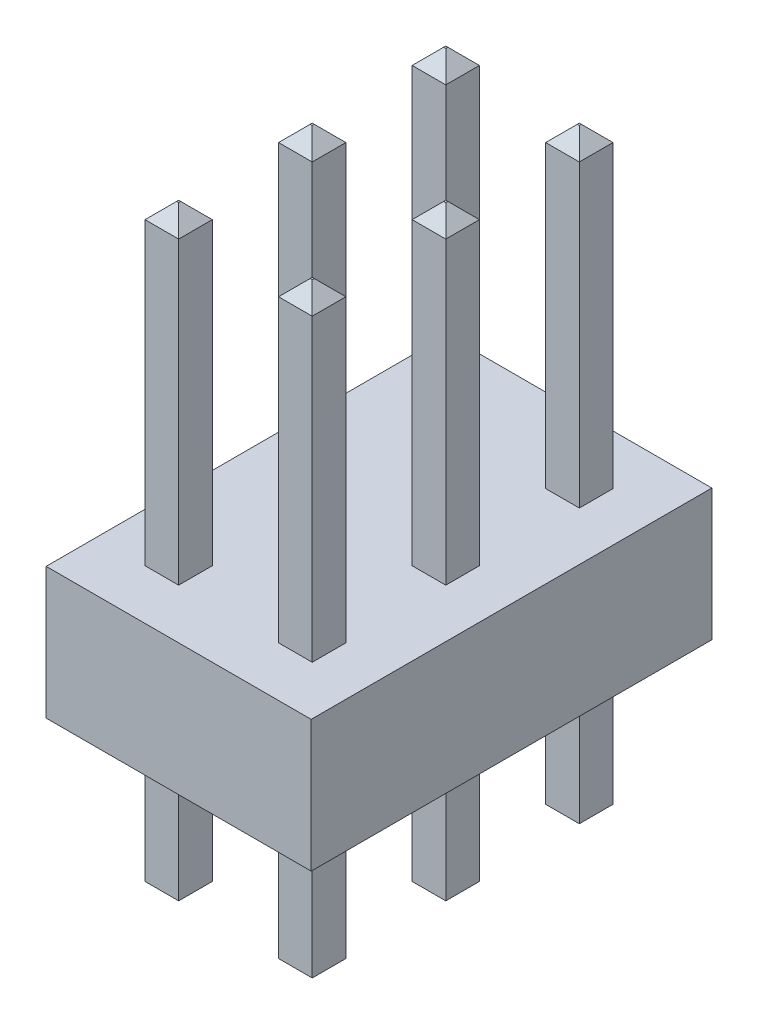
SolidWorks part; units mm, degrees
ref_plane "Vorne" through (0, 0, 0) normal (0, 0, 1) x (1, 0, 0)
ref_plane "Oben" through (0, 0, 0) normal (0, 1, 0) x (1, 0, 0)
ref_plane "Rechts" through (0, 0, 0) normal (1, 0, 0) x (0, 0, -1)
sketch "Skizze1" plane through (0, 0, 0) normal (0, 0, 1) x (1, 0, 0)
  line L1 (0, 0) -> (5.04, 0)
  line L2 (0, 0) -> (0, 2.5)
  line L3 (0, 2.5) -> (5.04, 2.5)
  line L4 (5.04, 0) -> (5.04, 2.5)
  dimension "D1" = 5.04
  dimension "D2" = 2.5
extrude "Aufsatz-Linear austragen1" add sketch "Skizze1" along normal blind 7.62
sketch "Skizze2" plane through (0, 2.5, 0) normal (0, 1, 0) x (1, 0, 0)
  line L0 (5.04, 0) -> (0, 0) construction
  line L1 (0, -7.62) -> (0, 0) construction
  line L2 (3.47, -0.95) -> (4.11, -0.95)
  line L3 (3.47, -0.95) -> (3.47, -1.59)
  line L4 (3.47, -1.59) -> (4.11, -1.59)
  line L5 (4.11, -0.95) -> (4.11, -1.59)
  line L6 (3.47, -0.95) -> (4.11, -1.59) construction
  line L7 (0.93, -0.95) -> (1.57, -0.95)
  line L8 (0.93, -0.95) -> (0.93, -1.59)
  line L9 (0.93, -1.59) -> (1.57, -1.59)
  line L10 (1.57, -0.95) -> (1.57, -1.59)
  line L11 (0.93, -0.95) -> (1.57, -1.59) construction
  line L12 (0.93, -1.59) -> (1.57, -0.95) construction
  line L13 (3.47, -1.59) -> (4.11, -0.95) construction
  line L14 (0.93, -3.49) -> (1.57, -3.49)
  line L15 (0.93, -3.49) -> (0.93, -4.13)
  line L16 (0.93, -4.13) -> (1.57, -4.13)
  line L17 (1.57, -3.49) -> (1.57, -4.13)
  line L18 (0.93, -3.49) -> (1.57, -4.13) construction
  line L19 (0.93, -4.13) -> (1.57, -3.49) construction
  line L20 (3.47, -3.49) -> (4.11, -3.49)
  line L21 (3.47, -3.49) -> (3.47, -4.13)
  line L22 (3.47, -4.13) -> (4.11, -4.13)
  line L23 (4.11, -3.49) -> (4.11, -4.13)
  line L24 (3.47, -3.49) -> (4.11, -4.13) construction
  line L25 (3.47, -4.13) -> (4.11, -3.49) construction
  line L26 (0.93, -6.03) -> (1.57, -6.03)
  line L27 (0.93, -6.03) -> (0.93, -6.67)
  line L28 (0.93, -6.67) -> (1.57, -6.67)
  line L29 (1.57, -6.03) -> (1.57, -6.67)
  line L30 (0.93, -6.03) -> (1.57, -6.67) construction
  line L31 (0.93, -6.67) -> (1.57, -6.03) construction
  line L32 (3.47, -6.03) -> (4.11, -6.03)
  line L33 (3.47, -6.03) -> (3.47, -6.67)
  line L34 (3.47, -6.67) -> (4.11, -6.67)
  line L35 (4.11, -6.03) -> (4.11, -6.67)
  line L36 (3.47, -6.03) -> (4.11, -6.67) construction
  line L37 (3.47, -6.67) -> (4.11, -6.03) construction
  point P4 (3.79, -1.27)
  point P5 (1.25, -1.27)
  point P16 (1.25, -3.81)
  point P21 (3.79, -3.81)
  point P26 (1.25, -6.35)
  point P31 (3.79, -6.35)
  dimension "D1" = 1.27
  dimension "D2" = 1.25
  dimension "D3" = 0.64
  dimension "D4" = 0.64
  dimension "D5" = 2
  dimension "D6" = 3
extrude "Aufsatz-Linear austragen2" add sketch "Skizze2" along normal blind 6
chamfer "Fase1" distance 0.3 angle 45 24 edges at (1.57, 8.5, 6.35) (1.25, 8.5, 6.67) (0.93, 8.5, 6.35) (1.25, 8.5, 6.03) (4.11, 8.5, 6.35) (3.79, 8.5, 6.67) (3.47, 8.5, 6.35) (3.79, 8.5, 6.03) (4.11, 8.5, 3.81) (3.79, 8.5, 4.13) (3.79, 8.5, 3.49) (3.47, 8.5, 3.81) (1.57, 8.5, 3.81) (1.25, 8.5, 4.13) (0.93, 8.5, 3.81) (1.25, 8.5, 3.49) (1.57, 8.5, 1.27) (1.25, 8.5, 1.59) (0.93, 8.5, 1.27) (1.25, 8.5, 0.95) (3.79, 8.5, 1.59) (3.47, 8.5, 1.27) (3.79, 8.5, 0.95) (4.11, 8.5, 1.27)
sketch "Skizze3" plane through (0, 0, 0) normal (0, -1, 0) x (1, 0, 0)
  line L0 (0, 7.62) -> (0, 0) construction
  line L1 (0.93, 0.95) -> (1.57, 0.95)
  line L2 (0.93, 0.95) -> (0.93, 1.59)
  line L3 (0.93, 1.59) -> (1.57, 1.59)
  line L4 (1.57, 0.95) -> (1.57, 1.59)
  line L5 (0.93, 0.95) -> (1.57, 1.59) construction
  line L6 (0.93, 1.59) -> (1.57, 0.95) construction
  line L7 (0, 0) -> (5.04, 0) construction
  line L8 (3.47, 0.95) -> (4.11, 0.95)
  line L9 (3.47, 0.95) -> (3.47, 1.59)
  line L10 (3.47, 1.59) -> (4.11, 1.59)
  line L11 (4.11, 0.95) -> (4.11, 1.59)
  line L12 (3.47, 0.95) -> (4.11, 1.59) construction
  line L13 (3.47, 1.59) -> (4.11, 0.95) construction
  line L14 (0.93, 3.49) -> (1.57, 3.49)
  line L15 (0.93, 3.49) -> (0.93, 4.13)
  line L16 (0.93, 4.13) -> (1.57, 4.13)
  line L17 (1.57, 3.49) -> (1.57, 4.13)
  line L18 (0.93, 3.49) -> (1.57, 4.13) construction
  line L19 (0.93, 4.13) -> (1.57, 3.49) construction
  line L20 (3.47, 3.49) -> (4.11, 3.49)
  line L21 (3.47, 3.49) -> (3.47, 4.13)
  line L22 (3.47, 4.13) -> (4.11, 4.13)
  line L23 (4.11, 3.49) -> (4.11, 4.13)
  line L24 (3.47, 3.49) -> (4.11, 4.13) construction
  line L25 (3.47, 4.13) -> (4.11, 3.49) construction
  line L26 (0.93, 6.03) -> (1.57, 6.03)
  line L27 (0.93, 6.03) -> (0.93, 6.67)
  line L28 (0.93, 6.67) -> (1.57, 6.67)
  line L29 (1.57, 6.03) -> (1.57, 6.67)
  line L30 (0.93, 6.03) -> (1.57, 6.67) construction
  line L31 (0.93, 6.67) -> (1.57, 6.03) construction
  line L32 (3.47, 6.03) -> (4.11, 6.03)
  line L33 (3.47, 6.03) -> (3.47, 6.67)
  line L34 (3.47, 6.67) -> (4.11, 6.67)
  line L35 (4.11, 6.03) -> (4.11, 6.67)
  line L36 (3.47, 6.03) -> (4.11, 6.67) construction
  line L37 (3.47, 6.67) -> (4.11, 6.03) construction
  point P0 (1.25, 1.27)
  point P11 (3.79, 1.27)
  point P16 (1.25, 3.81)
  point P21 (3.79, 3.81)
  point P26 (1.25, 6.35)
  point P31 (3.79, 6.35)
  dimension "D1" = 0.64
  dimension "D2" = 0.64
  dimension "D3" = 1.25
  dimension "D4" = 1.27
  dimension "D5" = 2
  dimension "D6" = 3
extrude "Aufsatz-Linear austragen3" add sketch "Skizze3" along normal blind 3
chamfer "Fase2" distance 0.3 angle 45 24 edges at (1.25, -3, 3.49) (0.93, -3, 3.81) (1.25, -3, 4.13) (1.57, -3, 3.81) (1.25, -3, 6.03) (0.93, -3, 6.35) (1.25, -3, 6.67) (1.57, -3, 6.35) (3.79, -3, 6.67) (3.47, -3, 6.35) (3.79, -3, 6.03) (4.11, -3, 6.35) (3.79, -3, 3.49) (3.47, -3, 3.81) (3.79, -3, 4.13) (4.11, -3, 3.81) (1.25, -3, 0.95) (0.93, -3, 1.27) (1.25, -3, 1.59) (1.57, -3, 1.27) (3.47, -3, 1.27) (3.79, -3, 1.59) (3.79, -3, 0.95) (4.11, -3, 1.27)
